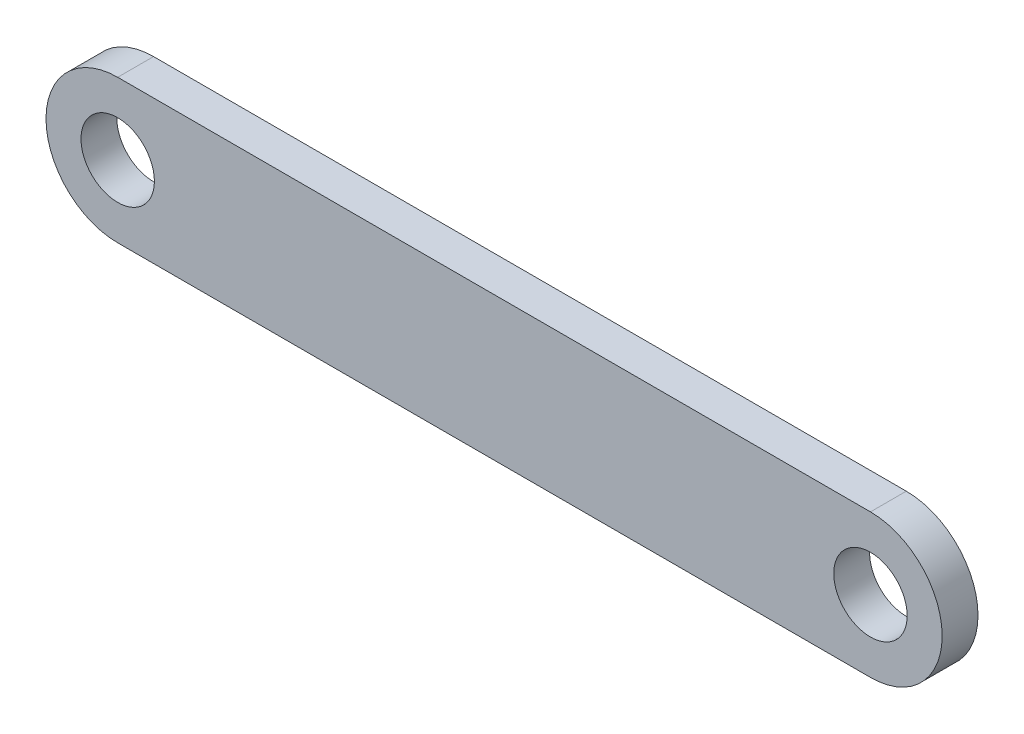
SolidWorks part; units mm, degrees
ref_plane "Front Plane" through (0, 0, 0) normal (0, 0, 1) x (1, 0, 0)
ref_plane "Top Plane" through (0, 0, 0) normal (0, 1, 0) x (1, 0, 0)
ref_plane "Right Plane" through (0, 0, 0) normal (1, 0, 0) x (0, 0, -1)
sketch "Sketch1" plane through (0, 0, 0) normal (0, 0, 1) x (1, 0, 0)
  line L0 (0, 0) -> (66.675, 0) construction
  line L1 (0, 0) -> (66.675, 0) construction
  line L2 (0, 6.35) -> (66.675, 6.35)
  line L3 (0, -6.35) -> (66.675, -6.35)
  circle A0 centre (0, 0) radius 3.2512
  circle A1 centre (66.675, 0) radius 3.2512
  arc A2 (0, 6.35) -> (0, -6.35) centre (0, 0) ccw
  arc A3 (66.675, -6.35) -> (66.675, 6.35) centre (66.675, 0) ccw
  point P5 (33.3375, 0)
  dimension "D2" = 6.5024
  dimension "D3" = 6.35
  dimension "D1" = 66.675
extrude "Boss-Extrude1" add sketch "Sketch1" along normal blind 3.175
